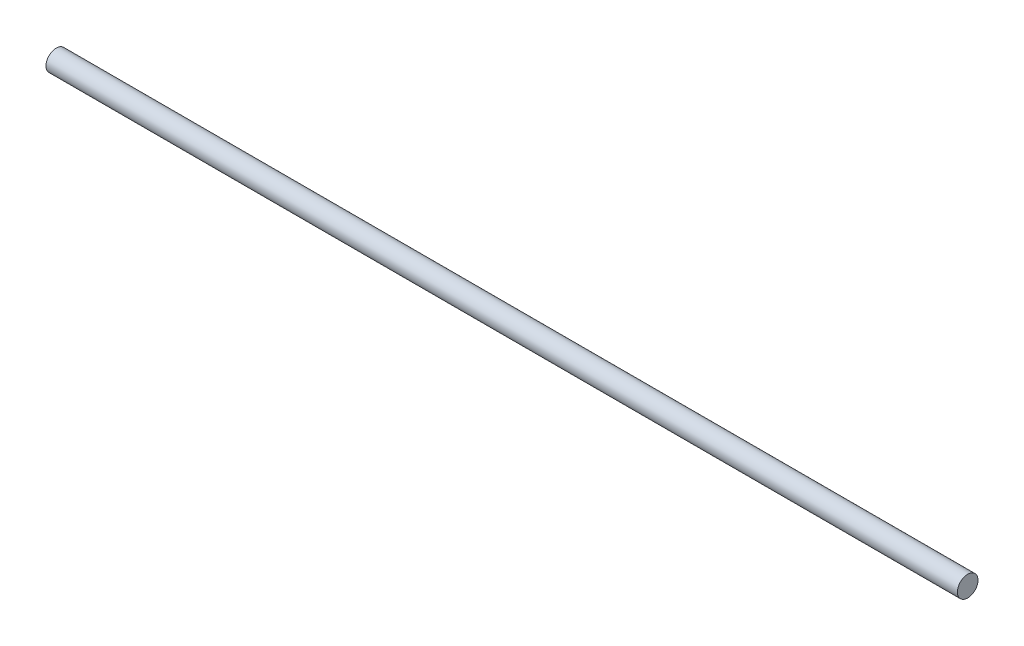
SolidWorks part; units mm, degrees
material "6061-T6 (SS)"
ref_plane "Front Plane" through (0, 0, 0) normal (0, 0, 1) x (1, 0, 0)
ref_plane "Top Plane" through (0, 0, 0) normal (0, 1, 0) x (1, 0, 0)
ref_plane "Right Plane" through (0, 0, 0) normal (1, 0, 0) x (0, 0, -1)
sketch "Sketch2" plane through (0, 0, 0) normal (1, 0, 0) x (0, 0, -1)
  circle A0 centre (0, 0) radius 3.175
  dimension "D1" = 6.35
extrude "Boss-Extrude2" add sketch "Sketch2" along normal blind 280.7475
equation "\"d\"= 0.25"
equation "\"A\"= 3.14159 * ( \"d\" / 2 ) ^ 2in"
equation "\"delf\"= .009in"
equation "\"E\"= 10007604"
equation "\"F\"= 400"
equation "\"L\"= ( \"delf\" * \"E\" * \"A\" ) / \"F\""
equation "\"D1@Boss-Extrude2\"=\"L\""
equation "\"D1@Sketch2\"=\"d\""
